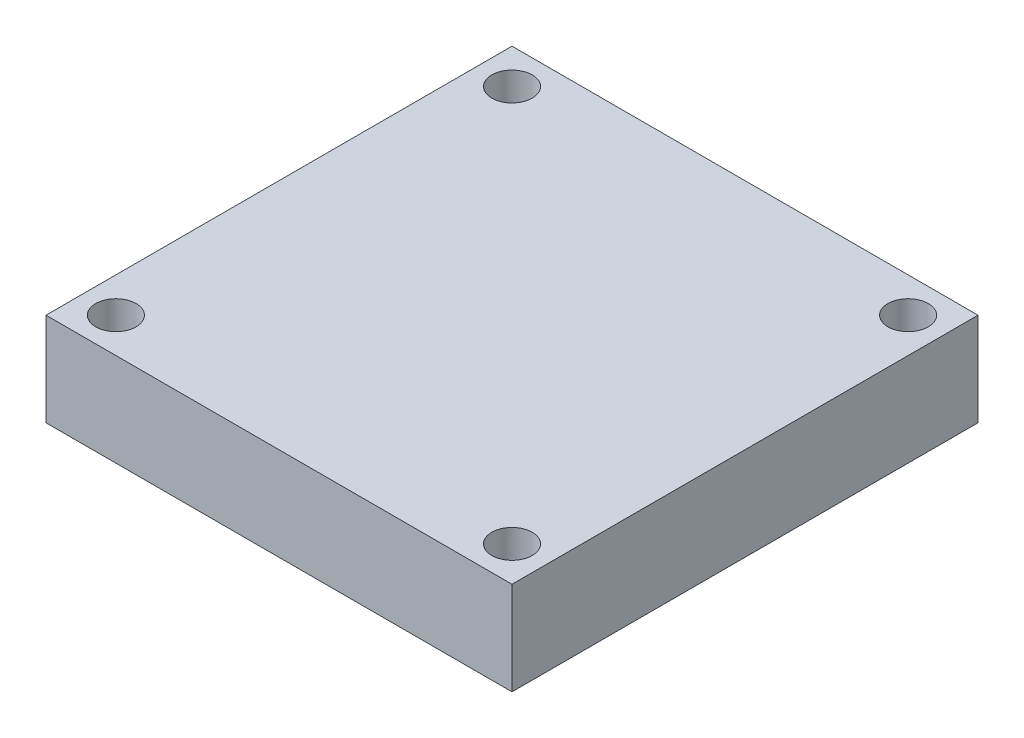
SolidWorks part; units mm, degrees
ref_plane "Front Plane" through (0, 0, 0) normal (0, 0, 1) x (1, 0, 0)
ref_plane "Top Plane" through (0, 0, 0) normal (0, 1, 0) x (1, 0, 0)
ref_plane "Right Plane" through (0, 0, 0) normal (1, 0, 0) x (0, 0, -1)
sketch "Sketch1" plane through (0, 0, 0) normal (0, 1, 0) x (1, 0, 0)
  line L1 (15, -15) -> (-15, -15)
  line L2 (15, -15) -> (15, 15)
  line L3 (15, 15) -> (-15, 15)
  line L4 (-15, -15) -> (-15, 15)
  line L5 (15, -15) -> (-15, 15) construction
  line L6 (15, 15) -> (-15, -15) construction
  line L7 (12.75, -12.75) -> (-12.75, -12.75) construction
  line L8 (12.75, -12.75) -> (12.75, 12.75) construction
  line L9 (12.75, 12.75) -> (-12.75, 12.75) construction
  line L10 (-12.75, -12.75) -> (-12.75, 12.75) construction
  line L11 (12.75, -12.75) -> (-12.75, 12.75) construction
  line L12 (12.75, 12.75) -> (-12.75, -12.75) construction
  circle A0 centre (-12.75, 12.75) radius 1.3
  circle A1 centre (12.75, 12.75) radius 1.3
  circle A2 centre (12.75, -12.75) radius 1.3
  circle A3 centre (-12.75, -12.75) radius 1.3
  point P0 (0, 0)
  point P6 (0, 0)
  dimension "D5" = 2.6
  dimension "D6" = 2.6
  dimension "D7" = 2.6
  dimension "D8" = 2.6
  dimension "D1" = 30
  dimension "D2" = 30
  dimension "D3" = 25.5
  dimension "D4" = 25.5
extrude "Boss-Extrude1" add sketch "Sketch1" along normal blind 6
